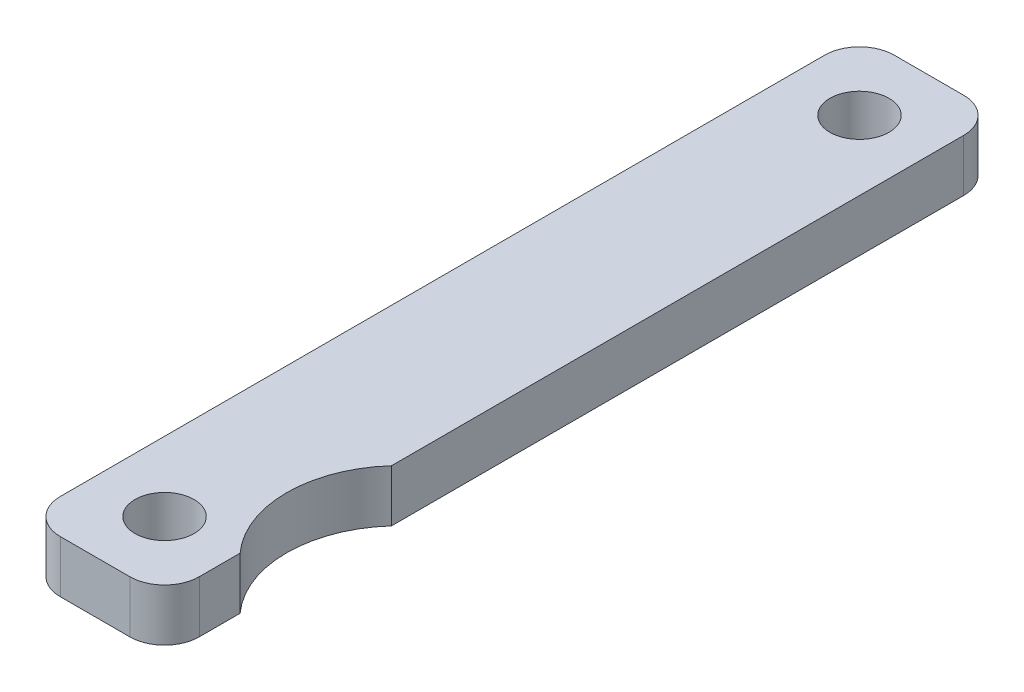
SolidWorks part; units mm, degrees
ref_plane "前基準面" through (0, 0, 0) normal (0, 0, 1) x (1, 0, 0)
ref_plane "上基準面" through (0, 0, 0) normal (0, 1, 0) x (1, 0, 0)
ref_plane "右基準面" through (0, 0, 0) normal (1, 0, 0) x (0, 0, -1)
sketch "草圖1" plane through (0, 0, 0) normal (0, 1, 0) x (1, 0, 0)
  line L0 (0, 24) -> (0, -24) construction
  line L1 (-2, 24) -> (2, 24)
  line L2 (-4, 22) -> (-4, -22)
  line L3 (-2, -24) -> (2, -24)
  line L4 (4, 22) -> (4, -22)
  line L5 (-4, 24) -> (4, -24) construction
  line L6 (-4, -24) -> (4, 24) construction
  line L7 (-4, 0) -> (4, 0) construction
  arc A0 (2, -24) -> (4, -22) centre (2, -22) ccw
  arc A1 (-4, -22) -> (-2, -24) centre (-2, -22) ccw
  arc A2 (2, 24) -> (4, 22) centre (2, 22) cw
  arc A3 (-2, 24) -> (-4, 22) centre (-2, 22) ccw
  circle A4 centre (0, 20) radius 1.7
  circle A5 centre (0, -20) radius 1.7
  point P0 (0, 0)
  dimension "D3" = 2
  dimension "D4" = 3.4
  dimension "D1" = 48
  dimension "D2" = 8
  dimension "D5" = 4
extrude "填料-伸長1" add sketch "草圖1" along normal blind 3
surface "曲面-偏移1" parameters "D1"=0
sketch "草圖2" plane through (0, 3, 0) normal (0, 1, 0) x (1, 0, 0)
  line L0 (4, -22) -> (4, 22) construction
  line L1 (4, -10.9369) -> (8.6059, -21.7904)
  arc A0 (3.8165, -12.1731) -> (8.626, -21.1907) centre (8.8235, -15.294) ccw construction
  arc A1 (3.8165, -12.1731) -> (8.626, -21.1907) centre (8.8235, -15.294) ccw construction
  arc A2 (4, -10.9369) -> (8.6059, -21.7904) centre (8.8235, -15.294) ccw
  arc A3 (3.3073, -11.8557) -> (8.6059, -21.7904) centre (8.8235, -15.294) ccw construction
  dimension "D1" = 0.6
extrude "除料-伸長1" cut sketch "草圖2" against normal up to surface (3 mm away) up to face at (0, 0, 0)
